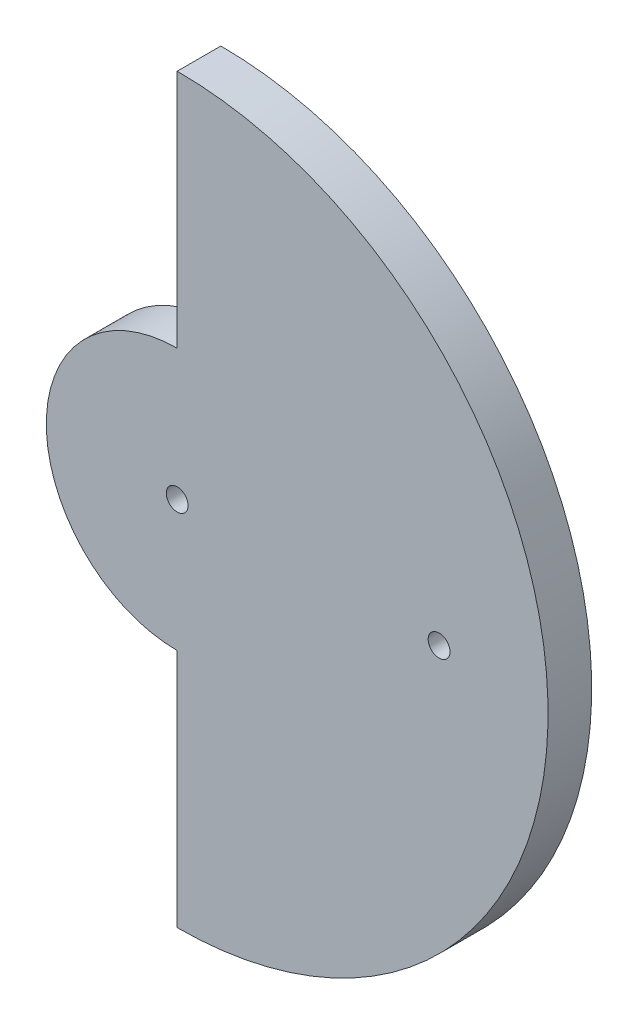
SolidWorks part; units mm, degrees
ref_plane "前视基准面" through (0, 0, 0) normal (0, 0, 1) x (1, 0, 0)
ref_plane "上视基准面" through (0, 0, 0) normal (0, 1, 0) x (1, 0, 0)
ref_plane "右视基准面" through (0, 0, 0) normal (1, 0, 0) x (0, 0, -1)
sketch "草图1" plane through (0, 0, 0) normal (0, 0, 1) x (1, 0, 0)
  circle A0 centre (0, 0) radius 85
extrude "凸台-拉伸1" add sketch "草图1" along normal blind 10
sketch "草图2" plane through (0, 0, 10) normal (0, 0, 1) x (1, 0, 0)
  line L0 (0, 0) -> (80, 0)
  circle A0 centre (0, 0) radius 2.5
  circle A1 centre (80, 0) radius 2.5
extrude "切除-拉伸1" cut sketch "草图2" against normal through all
sketch "草图3" plane through (0, 0, 0) normal (0, 0, -1) x (-1, 0, 0)
  line L0 (-80, 0) -> (-60.0255, 1.0093)
  circle A0 centre (-60.0255, 1.0093) radius 2.5
extrude "切除-拉伸2" cut sketch "草图3" against normal through all
sketch "草图4" plane through (0, 0, 0) normal (0, 0, -1) x (-1, 0, 0)
  line L0 (0, 85) -> (0, -85)
  circle A0 centre (0, 0) radius 30
  circle A1 centre (0, 0) radius 85 construction
  circle M4 centre (0, 0) radius 85
extrude "切除-拉伸3" cut sketch "草图4" against normal through all contours A0 L0 M4
sketch "草图5" plane through (0, 0, 0) normal (0, 0, -1) x (-1, 0, 0)
  circle A0 centre (-80, 0) radius 2.5
extrude "凸台-拉伸2" add sketch "草图5" against normal blind 10
